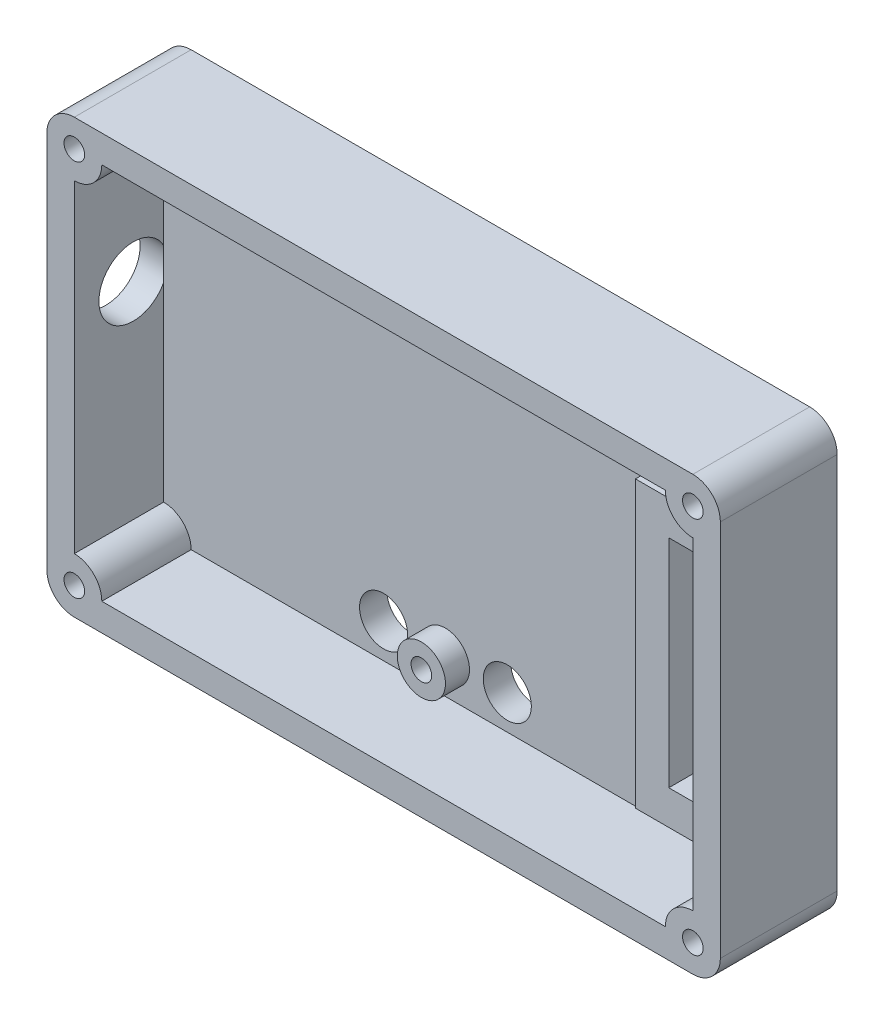
SolidWorks part; units mm, degrees
ref_plane "Plan de face" through (0, 0, 0) normal (0, 0, 1) x (1, 0, 0)
ref_plane "Plan de dessus" through (0, 0, 0) normal (0, 1, 0) x (1, 0, 0)
ref_plane "Plan de droite" through (0, 0, 0) normal (1, 0, 0) x (0, 0, -1)
sketch "Esquisse1" plane through (0, 0, 0) normal (0, 0, 1) x (1, 0, 0)
  line L1 (-13.886, 49.2609) -> (84.114, 49.2609)
  line L2 (-13.886, 49.2609) -> (-13.886, -13.7391)
  line L3 (-13.886, -13.7391) -> (84.114, -13.7391)
  line L4 (84.114, 49.2609) -> (84.114, -13.7391)
  line L5 (-9.886, 45.2609) -> (80.114, 45.2609)
  line L6 (-9.886, 45.2609) -> (-9.886, -9.7391)
  line L7 (-9.886, -9.7391) -> (80.114, -9.7391)
  line L8 (80.114, 45.2609) -> (80.114, -9.7391)
  dimension "D1" = 4
  dimension "D2" = 4
  dimension "D3" = 4
  dimension "D4" = 4
  dimension "D5" = 55
  dimension "D6" = 90
extrude "Boss.-Extru.1" add sketch "Esquisse1" along normal blind 13
sketch "Esquisse2" plane through (0, 0, 0) normal (0, 0, -1) x (-1, 0, 0)
  line L1 (13.886, 49.2609) -> (-84.114, 49.2609)
  line L2 (13.886, 49.2609) -> (13.886, -13.7391)
  line L3 (13.886, -13.7391) -> (-84.114, -13.7391)
  line L4 (-84.114, 49.2609) -> (-84.114, -13.7391)
extrude "Boss.-Extru.2" add sketch "Esquisse2" along normal blind 4
sketch "Esquisse3" plane through (0, 0, 0) normal (0, 0, 1) x (1, 0, 0)
  line L0 (-9.886, 45.2609) -> (-9.886, -9.7391) construction
  line L6 (75.614, 33.5109) -> (100.8214, 33.5109) construction
  line L8 (65.114, 73.2277) -> (65.114, -29.2612) construction
  line L9 (-31.8284, 33.5109) -> (65.7669, 33.5109) construction
  line L10 (-34.862, 2.0109) -> (65.7669, 2.0109) construction
  line L12 (80.114, 2.0109) -> (80.114, 33.5109)
  line L13 (80.114, -9.7391) -> (80.114, 45.2609) construction
  line L14 (80.114, -9.7391) -> (80.114, 45.2609) construction
  line L16 (80.114, 33.5109) -> (80.114, 38.5109)
  line L17 (80.114, 38.5109) -> (65.7669, 38.5109)
  line L18 (65.7669, 33.5109) -> (65.7669, 38.5109)
  line L21 (80.114, 2.0109) -> (80.114, -2.9891)
  line L22 (80.114, -2.9891) -> (65.7669, -2.9891)
  line L23 (65.7669, 2.0109) -> (65.7669, -2.9891)
  line L24 (75.614, 2.0109) -> (75.614, 33.5109)
  line L26 (65.7669, 2.0109) -> (65.7669, 33.5109)
  line L28 (70.614, 2.0109) -> (70.614, 33.5109)
  line L29 (70.614, 2.0109) -> (75.614, 2.0109)
  line L30 (80.114, 2.0109) -> (110.1979, 2.0109) construction
  line L31 (75.614, 33.5109) -> (70.614, 33.5109)
  point P20 (80.114, 17.7609)
  dimension "D1" = 4.5
  dimension "D2" = 5
  dimension "D3" = 75
  dimension "D4" = 31.5
  dimension "D5" = 15.75
  dimension "D6" = 5
  dimension "D7" = 5
extrude "Boss.-Extru.3" add sketch "Esquisse3" along normal blind 7
fillet "Congé2" radius 4 4 edges at (84.114, 49.2609, 4.5) (84.114, -13.7391, 4.5) (-13.886, -13.7391, 4.5) (-13.886, 49.2609, 4.5)
sketch "Esquisse6" plane through (0, 0, 13) normal (0, 0, 1) x (1, 0, 0)
  circle A1 centre (-9.886, 45.2609) radius 4
  circle A2 centre (-9.886, -9.7391) radius 4
  circle A3 centre (80.114, -9.7391) radius 4
  circle A4 centre (80.114, 45.2609) radius 4
  dimension "D1" = 8
  dimension "D2" = 8
  dimension "D3" = 8
extrude "Boss.-Extru.5" add sketch "Esquisse6" against normal up to surface (17 mm away) up to face at (35.114, 17.7609, -4)
sketch "Esquisse7" plane through (0, 0, 13) normal (0, 0, 1) x (1, 0, 0)
  circle A0 centre (80.114, -9.7391) radius 1.5
  circle A1 centre (-9.886, -9.7391) radius 1.5
  circle A2 centre (-9.886, 45.2609) radius 1.5
  circle A3 centre (80.114, 45.2609) radius 1.5
  dimension "D1" = 3
  dimension "D2" = 3
  dimension "D3" = 3
  dimension "D4" = 3
extrude "Enlèv. mat.-Extru.2" cut sketch "Esquisse7" against normal blind 83.442
sketch "Esquisse8" plane through (0, 0, 0) normal (0, 0, 1) x (1, 0, 0)
  line L0 (-5.886, -9.7391) -> (76.114, -9.7391) construction
  line L1 (-13.886, 45.2609) -> (-13.886, -9.7391) construction
  circle A0 centre (22.114, -4.7391) radius 3.5
  circle A1 centre (40.114, -4.7391) radius 3.5
  point P4 (0, 0)
  point P6 (33.9319, -2.7896)
  dimension "D1" = 7
  dimension "D2" = 7
  dimension "D3" = 18
  dimension "D4" = 5
  dimension "D5" = 36
extrude "Enlèv. mat.-Extru.3" cut sketch "Esquisse8" against normal blind 10
sketch "Esquisse9" plane through (0, 0, 0) normal (0, 0, 1) x (1, 0, 0)
  circle A0 centre (31.1132, -4.6174) radius 3.5
  circle A1 centre (31.1132, -4.6174) radius 1.5
  circle A2 centre (22.114, -4.7391) radius 3.5 construction
  dimension "D1" = 3
  dimension "D2" = 7
  dimension "D3" = 9
extrude "Boss.-Extru.6" add sketch "Esquisse9" along normal blind 3.5
sketch "Esquisse10" plane through (-13.886, 0, 0) normal (-1, 0, 0) x (0, 0, 1)
  circle A0 centre (4.4244, 24.2666) radius 5
  dimension "D1" = 10
extrude "Enlèv. mat.-Extru.4" cut sketch "Esquisse10" against normal blind 4
